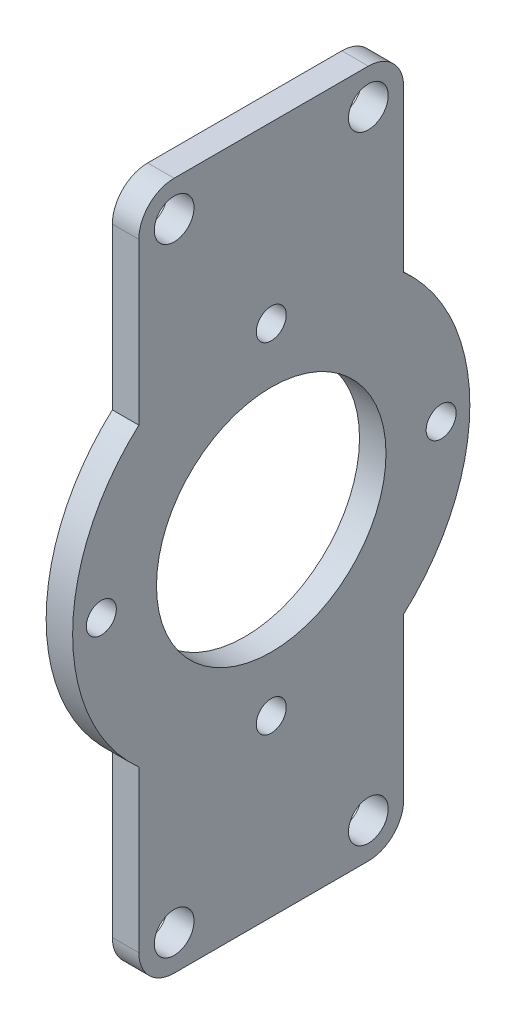
SolidWorks part; units mm, degrees
ref_plane "Спереди" through (0, 0, 0) normal (0, 0, 1) x (1, 0, 0)
ref_plane "Сверху" through (0, 0, 0) normal (0, 1, 0) x (1, 0, 0)
ref_plane "Справа" through (0, 0, 0) normal (1, 0, 0) x (0, 0, -1)
sketch "Эскиз1" plane through (0, 0, 0) normal (0, 1, 0) x (1, 0, 0)
  line L1 (0, 0) -> (3, 0)
  line L2 (0, 0) -> (0, -30)
  line L3 (0, -30) -> (3, -30)
  line L4 (3, 0) -> (3, -30)
  dimension "D1" = 3
  dimension "D2" = 30
extrude "Бобышка-Вытянуть1" add sketch "Эскиз1" along normal blind 78
sketch "Эскиз2" plane through (0, 0, 0) normal (-1, 0, 0) x (0, 0, 1)
  line L0 (30, 39) -> (0, 39) construction
  line L1 (30, 78) -> (30, 0) construction
  line L2 (0, 78) -> (0, 0) construction
  line L3 (15, 78) -> (15, 0) construction
  line L4 (0, 78) -> (30, 78) construction
  line L5 (0, 0) -> (30, 0) construction
  circle A0 centre (15, 39) radius 22.5
  dimension "D1" = 45
extrude "Бобышка-Вытянуть2" add sketch "Эскиз2" against normal up to surface (3 mm away) up to face at (3, 39, 15)
sketch "Эскиз3" plane through (0, 0, 0) normal (-1, 0, 0) x (0, 0, 1)
  circle A0 centre (15, 39) radius 13
  dimension "D1" = 26
extrude "Вырез-Вытянуть1" cut sketch "Эскиз3" against normal through all
sketch "Эскиз4" plane through (3, 0, 0) normal (-1, 0, 0) x (0, 0, 1)
  line L0 (15, 61.5) -> (15, 16.5) construction
  line L1 (15, 78) -> (15, 0) construction
  line L2 (37.5, 39) -> (-7.5, 39) construction
  circle A0 centre (15, 39) radius 19.25 construction
  circle A1 centre (15, 39) radius 22.5 construction
  dimension "D1" = 38.5
hole_wizard "Отверстие с зазором M31" positions "Эскиз6" profile "Эскиз5" hole size "M3" standard "Ansi Metric" end condition through all
sketch "Эскиз6" plane through (3, -25.0247, 7.2629) normal (-1, 0, 0) x (0, 0, 1)
  line L0 (7.7371, 86.5247) -> (7.7371, 41.5247) construction
  line L1 (30.2371, 64.0247) -> (-14.7629, 64.0247) construction
  circle A0 centre (7.7371, 64.0247) radius 19.25 construction
  point P0 (7.7371, 83.2747)
  point P6 (-11.5129, 64.0247)
  point P10 (7.7371, 44.7747)
  point P12 (26.9871, 64.0247)
sketch "Эскиз5" plane through (3, 58.25, 15) normal (0, 1, 0) x (0, 0, -1)
  line L0 (0, 0) -> (0, 3)
  line L1 (0, 3) -> (1.7, 3)
  line L2 (1.7, 3) -> (1.7, 0)
  line L5 (1.7, 0) -> (0, 0)
  line L11 (0, -6.35) -> (0, 107.95) construction
  dimension "Диаметр сквозного отверстия" = 3.4
  dimension "Глубина сквозного отверстия" = 3
sketch "Эскиз8" plane through (3, 0, 0) normal (1, 0, 0) x (0, 0, -1)
  line L0 (-15, 78) -> (-15, 0) construction
  line L1 (-30, 78) -> (0, 78) construction
  line L2 (-30, 0) -> (0, 0) construction
  line L3 (19.447, 39) -> (-49.447, 39) construction
  line L4 (0, 78) -> (0, 55.7705) construction
  line L5 (-26, 74) -> (-4, 74) construction
  line L6 (-26, 74) -> (-26, 4) construction
  line L7 (-26, 4) -> (-4, 4) construction
  line L8 (-4, 74) -> (-4, 4) construction
  line L9 (-26, 74) -> (-4, 4) construction
  line L10 (-26, 4) -> (-4, 74) construction
  point P8 (-15, 39)
  point P9 (-15, 39)
  dimension "D1" = 4
  dimension "D2" = 70
hole_wizard "Отверстие с зазором M41" positions "Эскиз10" profile "Эскиз9" hole size "M4" standard "Ansi Metric" end condition through all
sketch "Эскиз10" plane through (3, 0, 0) normal (1, 0, 0) x (0, 0, -1)
  point P0 (-26, 74)
  point P3 (-4, 74)
  point P6 (-4, 4)
  point P9 (-26, 4)
sketch "Эскиз9" plane through (3, 74, 26) normal (0, 1, 0) x (0, 0, -1)
  line L0 (0, 0) -> (0, 3)
  line L1 (0, 3) -> (2.25, 3)
  line L2 (2.25, 3) -> (2.25, 0)
  line L5 (2.25, 0) -> (0, 0)
  line L11 (0, -6.35) -> (0, 107.95) construction
  dimension "Диаметр сквозного отверстия" = 4.5
  dimension "Глубина сквозного отверстия" = 3
fillet "Скругление1" radius 4 4 edges at (1.5, 0, 0) (1.5, 0, 30) (1.5, 78, 30) (1.5, 78, 0)
